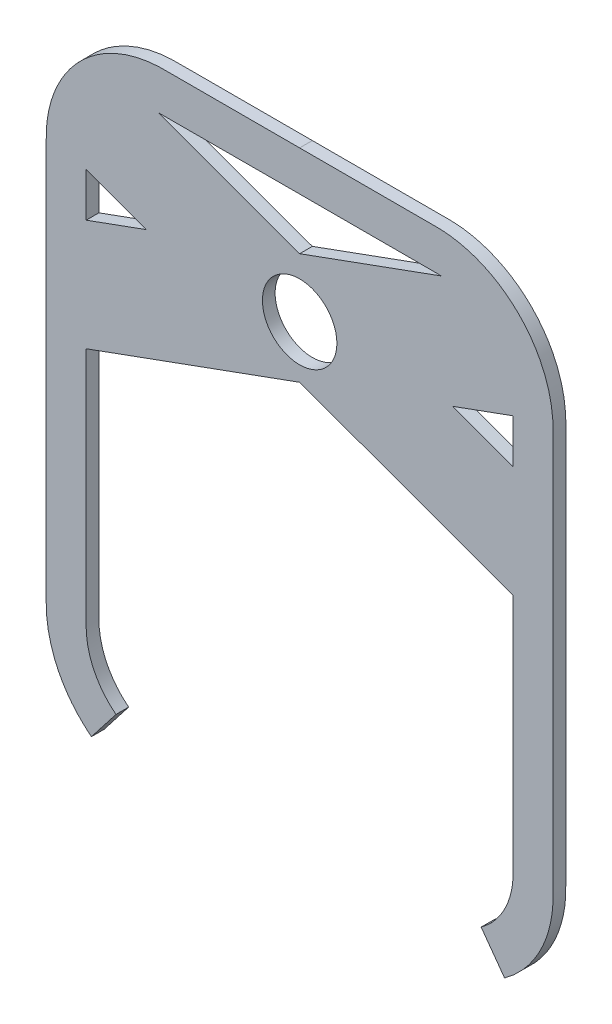
SolidWorks part; units mm, degrees
material "Фанера"
ref_plane "Front Plane" through (0, 0, 0) normal (0, 0, 1) x (1, 0, 0)
ref_plane "Top Plane" through (0, 0, 0) normal (0, 1, 0) x (1, 0, 0)
ref_plane "Right Plane" through (0, 0, 0) normal (1, 0, 0) x (0, 0, -1)
sketch "Эскиз1" plane through (0, 0, 0) normal (0, 0, 1) x (1, 0, 0)
  line L0 (-45.8381, 1.6179) -> (-40.4357, 8.5643)
  line L1 (39.9636, 8.2102) -> (45.1219, 1.0805)
  line L2 (0, 155.6618) -> (0, 34.4561) construction
  line L3 (0, 128.0052) -> (86.618, 128.0052) construction
  line L4 (-31.1435, 127.9666) -> (0, 116.6313)
  line L5 (-47, 109.2179) -> (-33.6841, 104.3713)
  line L6 (47, 109.2179) -> (33.6841, 104.3713)
  line L7 (31.1435, 127.9666) -> (0, 116.6313)
  line L8 (-33.6841, 104.3713) -> (-47, 99.5247)
  line L9 (0, 92.1113) -> (47, 75.0047)
  line L10 (33.6841, 104.3713) -> (47, 99.5247)
  line L11 (0, 92.1113) -> (-47, 75.0047)
  line L12 (-47, 109.2179) -> (-50.4323, 120.4968)
  line L13 (-50.4323, 120.4968) -> (-33.6841, 132.0604)
  line L14 (-33.6841, 132.0604) -> (-31.1435, 127.9666)
  line L15 (-47, 99.5247) -> (-51.8778, 93.1536)
  line L16 (-51.8778, 93.1536) -> (-50.4323, 75.0047)
  line L17 (-50.4323, 75.0047) -> (-47, 75.0047)
  line L18 (31.1435, 127.9666) -> (40.7246, 130.8823)
  line L19 (40.7246, 130.8823) -> (51.2312, 117.7263)
  line L20 (51.2312, 117.7263) -> (47, 109.2179)
  line L21 (47, 99.5247) -> (50.1131, 83.558)
  line L22 (50.1131, 83.558) -> (47, 75.0047)
  circle A1 centre (0, 103.6369) radius 8.2
  circle A2 centre (0, 103.6369) radius 4.3081 construction
  spline S2 degree 3 poles (44.653, 1.7287) (45.7274, 2.506) (47.9893, 4.4335) (50.9208, 8.0055) (53.2459, 12.3555) (54.6778, 17.0756) (55, 20.3481) (55, 51.6579) (55, 81.3315) (55, 112.6414) (54.6778, 115.9139) (53.2459, 120.6339) (50.9208, 124.984) (47.7917, 128.7968) (43.9788, 131.926) (39.6288, 134.2511) (34.9087, 135.6829) (31.6362, 136.0052) (20, 136.0052) (10, 136.0052) (0, 136.0052) knots 0 0 0 0 0.017483 0.039054 0.060625 0.082196 0.103767 0.103767 0.494964 0.494964 0.516535 0.538106 0.559677 0.581248 0.602819 0.62439 0.645961 0.667533 0.667533 0.799365 0.799365 0.799365 0.799365 construction
  spline S3 degree 3 poles (0, 136.0052) (-10, 136.0052) (-20, 136.0052) (-31.6362, 136.0052) (-34.9087, 135.6829) (-39.6288, 134.2511) (-43.9788, 131.926) (-47.7917, 128.7968) (-50.9208, 124.984) (-53.2459, 120.6339) (-54.6778, 115.9139) (-55, 112.6414) (-55, 81.3315) (-55, 51.6579) (-55, 20.3481) (-54.6778, 17.0756) (-53.2459, 12.3555) (-50.9208, 8.0055) (-48.1737, 4.6582) (-46.1655, 2.8859) (-45.347, 2.2494) knots 0 0 0 0 0.131833 0.131833 0.153404 0.174975 0.196546 0.218117 0.239689 0.26126 0.282831 0.304402 0.304402 0.695598 0.695598 0.717169 0.73874 0.760311 0.781883 0.795553 0.795553 0.795553 0.795553 construction
  spline S4 degree 1 poles (45.1219, 1.0805) (0, 136.8052) knots 0 0 1 1 construction
  spline S5 degree 1 poles (0, 136.8052) (-45.8381, 1.6179) knots 0 0 1 1 construction
  spline S6 degree 3 poles (45.1219, 1.0805) (46.7028, 2.2243) (49.6149, 4.8819) (52.9632, 9.7416) (54.7718, 14.3199) (55.5688, 18.1517) (55.7992, 20.5977) (55.8001, 22.537) (55.7999, 24.4209) (55.8, 26.7948) (55.8, 29.6353) (55.8, 33.4256) (55.8, 38.1624) (55.8, 43.847) (55.8, 49.5315) (55.8, 57.1108) (55.8, 66.585) (55.8, 76.0591) (55.8, 83.6385) (55.8, 89.323) (55.8, 95.0076) (55.8001, 99.7443) (55.7999, 103.5347) (55.8004, 106.3748) (55.7989, 108.7501) (55.802, 110.6311) (55.7894, 112.5824) (55.5402, 115.0208) (54.7159, 118.8491) (52.8747, 123.4128) (49.4893, 128.2498) (45.1003, 132.1996) (40.7946, 134.5811) (37.0952, 135.8686) (34.2273, 136.5111) (31.7978, 136.7802) (29.8327, 136.8098) (27.9551, 136.8025) (25.5782, 136.806) (21.7918, 136.8047) (17.0531, 136.8053) (9.4744, 136.8051) (3.7897, 136.8052) (0, 136.8052) knots 0 0 0 0 0.02498 0.04996 0.074941 0.087431 0.099921 0.106166 0.112411 0.124901 0.137391 0.149881 0.174861 0.199841 0.224822 0.249802 0.299762 0.349722 0.374703 0.399683 0.424663 0.449643 0.462133 0.474623 0.487113 0.493358 0.499603 0.512094 0.524584 0.549564 0.574544 0.599524 0.624504 0.636994 0.649484 0.661975 0.66822 0.674465 0.686955 0.699445 0.724425 0.749405 0.799365 0.799365 0.799365 0.799365
  spline S7 degree 3 poles (0, 136.8052) (-3.7716, 136.8052) (-9.4292, 136.8051) (-16.9718, 136.8053) (-21.6877, 136.8049) (-25.4565, 136.8057) (-27.8209, 136.8036) (-29.6919, 136.8079) (-31.6381, 136.7905) (-34.0623, 136.5374) (-36.9193, 135.9176) (-40.6107, 134.6632) (-44.9145, 132.328) (-49.3184, 128.438) (-52.737, 123.6586) (-54.6206, 119.1402) (-55.4881, 115.3363) (-55.7654, 112.9236) (-55.8064, 110.9599) (-55.7963, 109.0933) (-55.8012, 106.7266) (-55.7997, 103.9009) (-55.8002, 100.1284) (-55.7999, 95.4143) (-55.8, 89.7568) (-55.8, 84.0995) (-55.8, 76.5563) (-55.8, 67.1273) (-55.8, 55.8125) (-55.8001, 46.3835) (-55.7999, 38.8403) (-55.8004, 33.1831) (-55.7989, 28.468) (-55.8015, 25.1689) (-55.7973, 23.2815) (-55.8144, 21.4024) (-55.6793, 18.9377) (-54.9979, 15.111) (-53.3484, 10.4948) (-50.1767, 5.5527) (-47.3711, 2.8101) (-45.8381, 1.6179) knots 0 0 0 0 0.049722 0.074583 0.099444 0.111875 0.124305 0.13052 0.136736 0.149166 0.161597 0.174027 0.198888 0.223749 0.24861 0.273471 0.285902 0.298332 0.304547 0.310763 0.323193 0.335624 0.348054 0.372915 0.397776 0.422637 0.447498 0.49722 0.546942 0.596664 0.621525 0.646386 0.671247 0.683678 0.689893 0.696108 0.708539 0.720969 0.745831 0.770692 0.795553 0.795553 0.795553 0.795553
  spline S8 degree 1 poles (39.9636, 8.2102) (0, 128.0052) knots 0 0 1 1 construction
  spline S9 degree 1 poles (0, 128.0052) (-40.4357, 8.5643) knots 0 0 1 1 construction
  spline S10 degree 3 poles (39.9636, 8.2102) (41.0054, 8.9639) (42.9242, 10.7147) (44.7631, 13.3844) (45.8458, 15.7264) (46.3523, 17.2593) (46.6512, 18.5129) (46.8213, 19.4635) (46.9374, 20.4231) (46.9834, 21.1505) (46.9969, 21.6291) (46.9997, 21.838) (47.0001, 21.9828) (47, 22.2422) (47, 22.6426) (47, 23.2426) (47, 24.1869) (47, 25.3727) (47, 27.2669) (47, 29.6358) (47, 33.4253) (47, 38.1625) (47, 43.847) (47, 49.5315) (47, 57.1108) (47, 65.1282) (47, 72.1981) (47, 75.9878) (47, 79.3394) (47, 83.6385) (47, 89.323) (47, 94.3816) (47, 98.019) (47, 99.9984) (47, 101.5718) (47, 103.619) (47, 105.9022) (47, 107.7987) (47, 108.9786) (47, 109.9351) (46.9998, 110.504) (47.0003, 111.0254) (46.9986, 111.3047) (46.9825, 111.8946) (46.9257, 112.6841) (46.7617, 113.9693) (46.4214, 115.5413) (45.8003, 117.3774) (44.7006, 119.7115) (42.8415, 122.3685) (39.9491, 124.9708) (37.1132, 126.5398) (34.6745, 127.3879) (33.1011, 127.7416) (31.8255, 127.9161) (31.0164, 127.9798) (30.4624, 128.0003) (30.1677, 128.0046) (30.0279, 128.0053) (29.7806, 128.0051) (29.4896, 128.0052) (29.0139, 128.0052) (28.1862, 128.0052) (27.0012, 128.0052) (25.1067, 128.0052) (22.738, 128.0052) (19.8958, 128.0052) (16.1061, 128.0052) (11.369, 128.0052) (5.6845, 128.0052) (1.8948, 128.0052) (0, 128.0052) knots 0 0 0 0 0.02498 0.04996 0.06245 0.074941 0.081186 0.087431 0.093676 0.099921 0.101482 0.103043 0.103824 0.104604 0.106166 0.109288 0.112411 0.118656 0.124901 0.137391 0.149881 0.174861 0.199841 0.224822 0.249802 0.299762 0.330517 0.343007 0.349722 0.374703 0.399683 0.424663 0.441391 0.447636 0.450758 0.462133 0.474623 0.480868 0.487113 0.490236 0.493358 0.49492 0.496481 0.499603 0.505848 0.512094 0.524584 0.537074 0.549564 0.574544 0.599524 0.624504 0.636994 0.649484 0.655729 0.661975 0.665097 0.666658 0.667439 0.66822 0.669781 0.671342 0.674465 0.68071 0.686955 0.699445 0.711935 0.724425 0.749405 0.774385 0.799365 0.799365 0.799365 0.799365
  spline S11 degree 3 poles (0, 128.0052) (-1.8858, 128.0052) (-5.6574, 128.0052) (-11.3148, 128.0052) (-16.0293, 128.0052) (-19.8009, 128.0052) (-22.6296, 128.0052) (-24.9866, 128.0052) (-26.8729, 128.0052) (-28.0504, 128.0051) (-28.9956, 128.0052) (-29.5789, 128.0049) (-30.0627, 128.0055) (-30.343, 128.0028) (-30.6865, 127.9927) (-31.015, 127.9754) (-31.3353, 127.9538) (-31.8833, 127.9053) (-32.9935, 127.7615) (-34.5576, 127.4202) (-36.9928, 126.5937) (-39.8265, 125.0554) (-42.729, 122.4922) (-44.606, 119.868) (-45.7266, 117.556) (-46.3656, 115.7381) (-46.7237, 114.1738) (-46.9027, 112.9043) (-46.9697, 112.1019) (-46.9927, 111.5459) (-46.9993, 111.2181) (-47.0002, 111.0008) (-46.9999, 110.6109) (-47, 110.1558) (-47, 109.7444) (-47, 109.3357) (-47, 108.8598) (-47, 107.972) (-47, 106.257) (-47, 103.9005) (-47, 100.1286) (-47, 95.4143) (-47, 89.7568) (-47, 84.0994) (-47, 76.5563) (-47, 67.1273) (-47, 57.6983) (-47, 50.1551) (-47, 44.4977) (-47, 38.8403) (-47, 34.1258) (-47, 30.3543) (-47, 27.9969) (-47, 26.1114) (-47, 24.6959) (-47, 23.5209) (-47, 22.6894) (-47, 22.2859) (-47, 22.0357) (-47, 21.8595) (-46.9975, 21.6672) (-46.9893, 21.3437) (-46.9628, 20.785) (-46.8911, 19.9846) (-46.7511, 19.0327) (-46.4933, 17.7782) (-46.0373, 16.2361) (-45.0362, 13.8731) (-43.2949, 11.1566) (-41.4459, 9.35) (-40.4357, 8.5643) knots 0 0 0 0 0.024861 0.049722 0.074583 0.087014 0.099444 0.111875 0.11809 0.124305 0.127413 0.13052 0.132074 0.133628 0.136736 0.138453 0.140007 0.142951 0.149166 0.161597 0.174027 0.198888 0.223749 0.24861 0.261041 0.273471 0.285902 0.292117 0.298332 0.30144 0.302994 0.304547 0.306101 0.307655 0.310702 0.311479 0.313033 0.316978 0.323193 0.335624 0.348054 0.372915 0.397776 0.422637 0.447498 0.49722 0.546942 0.571803 0.596664 0.621525 0.646386 0.658817 0.671247 0.677463 0.683678 0.689893 0.693001 0.694555 0.695332 0.696108 0.697662 0.699216 0.702324 0.708539 0.714754 0.720969 0.7334 0.745831 0.770692 0.795553 0.795553 0.795553 0.795553
  dimension "D3" = 16.4
  dimension "D4" = 20
  dimension "D1" = 0.8
  dimension "D2" = 8
extrude "Бобышка-Вытянуть1" add sketch "Эскиз1" along normal mid plane 2.8 contours L4 S11 L5 L8 L11 L9 S10 L10 L6 L7 A1 | S11 S10 L7 L18 L19 L20 L21 L22 L1 S6 S7 L0 L17 L16 L15 L12 L13 L14 | S11 L14 L13 L12 | S11 L15 L16 L17 | S10 L20 L19 L18 L7 | S10 L22 L21
